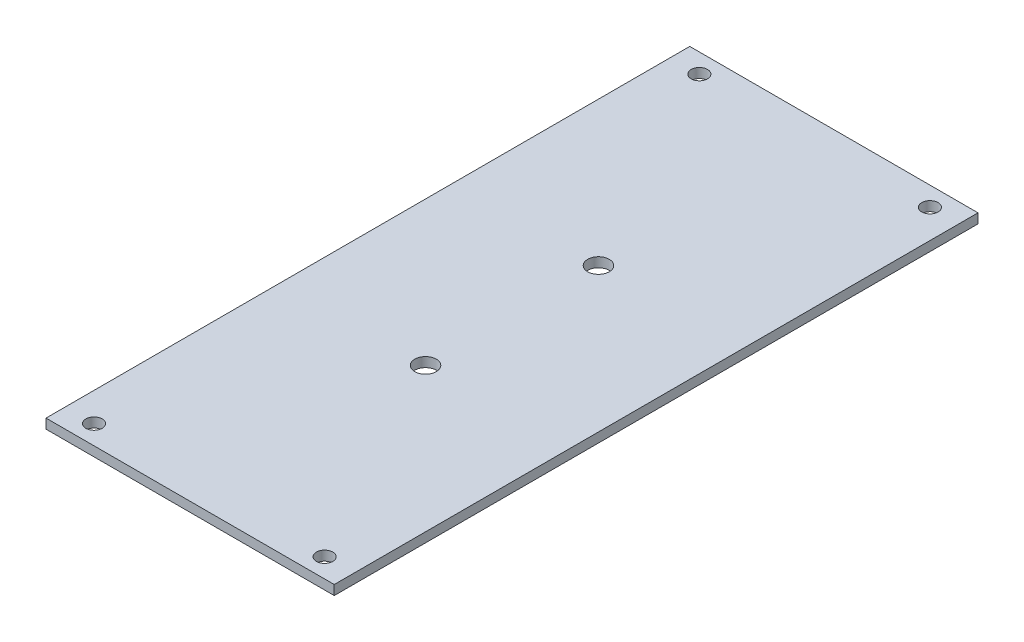
SolidWorks part; units mm, degrees
ref_plane "Front Plane" through (0, 0, 0) normal (0, 0, 1) x (1, 0, 0)
ref_plane "Top Plane" through (0, 0, 0) normal (0, 1, 0) x (1, 0, 0)
ref_plane "Right Plane" through (0, 0, 0) normal (1, 0, 0) x (0, 0, -1)
sketch "Sketch1" plane through (0, 0, 0) normal (0, 1, 0) x (1, 0, 0)
  line L1 (-30, 67) -> (30, 67)
  line L2 (-30, 67) -> (-30, -67)
  line L3 (-30, -67) -> (30, -67)
  line L4 (30, 67) -> (30, -67)
  line L5 (-30, 67) -> (30, -67) construction
  line L6 (-30, -67) -> (30, 67) construction
  point P0 (0, 0)
  dimension "D1" = 60
  dimension "D2" = 134
extrude "Boss-Extrude1" add sketch "Sketch1" along normal blind 2
hole_wizard "M4 Clearance Hole1" positions "Sketch3" profile "Sketch5" hole size "M4" standard "ANSI Metric"
sketch "Sketch3" plane through (182.3434, 2, 33.5535) normal (0, 1, 0) x (1, 0, 0)
  line L0 (-182.3434, 15.5535) -> (-182.3434, 51.5535) construction
  point P0 (-182.3434, 51.5535)
  point P2 (-182.3434, 15.5535)
  point P10 (-182.3434, 33.5535)
  dimension "D1" = 36
sketch "Sketch5" plane through (0, 2, -18) normal (1, 0, 0) x (0, 0, 1)
  line L0 (0, 0) -> (0, 18.7319)
  line L1 (0, 18.7319) -> (2.25, 17.38)
  line L2 (2.25, 17.38) -> (2.25, 0)
  line L5 (2.25, 0) -> (0, 0)
  line L10 (0, 18.7319) -> (-2.25, 17.38) construction
  line L11 (0, -6.35) -> (0, 107.95) construction
  dimension "Hole Dia." = 4.5
  dimension "Hole Depth" = 17.38
  dimension "Drill Angle" = 118
hole_wizard "M3 Clearance Hole1" positions "Sketch7" profile "Sketch9" hole size "M3" standard "ANSI Metric"
sketch "Sketch7" plane through (182.3434, 2, 33.5535) normal (0, 1, 0) x (1, 0, 0)
  line L0 (-158.3434, -29.4465) -> (-158.3434, 96.5535) construction
  line L1 (-158.3434, 96.5535) -> (-206.3434, 96.5535) construction
  line L2 (-206.3434, 96.5535) -> (-206.3434, -29.4465) construction
  line L3 (-206.3434, -29.4465) -> (-158.3434, -29.4465) construction
  point P2 (-206.3434, 96.5535)
  point P4 (-158.3434, 96.5535)
  point P6 (-158.3434, -29.4465)
  point P8 (-206.3434, -29.4465)
  point P26 (-206.3434, 33.5535)
  point P28 (-182.3434, 96.5535)
  dimension "D1" = 48
  dimension "D2" = 126
sketch "Sketch9" plane through (-24, 2, -63) normal (1, 0, 0) x (0, 0, 1)
  line L0 (0, 0) -> (0, 18.4015)
  line L1 (0, 18.4015) -> (1.7, 17.38)
  line L2 (1.7, 17.38) -> (1.7, 0)
  line L5 (1.7, 0) -> (0, 0)
  line L10 (0, 18.4015) -> (-1.7, 17.38) construction
  line L11 (0, -6.35) -> (0, 107.95) construction
  dimension "Hole Dia." = 3.4
  dimension "Hole Depth" = 17.38
  dimension "Drill Angle" = 118
